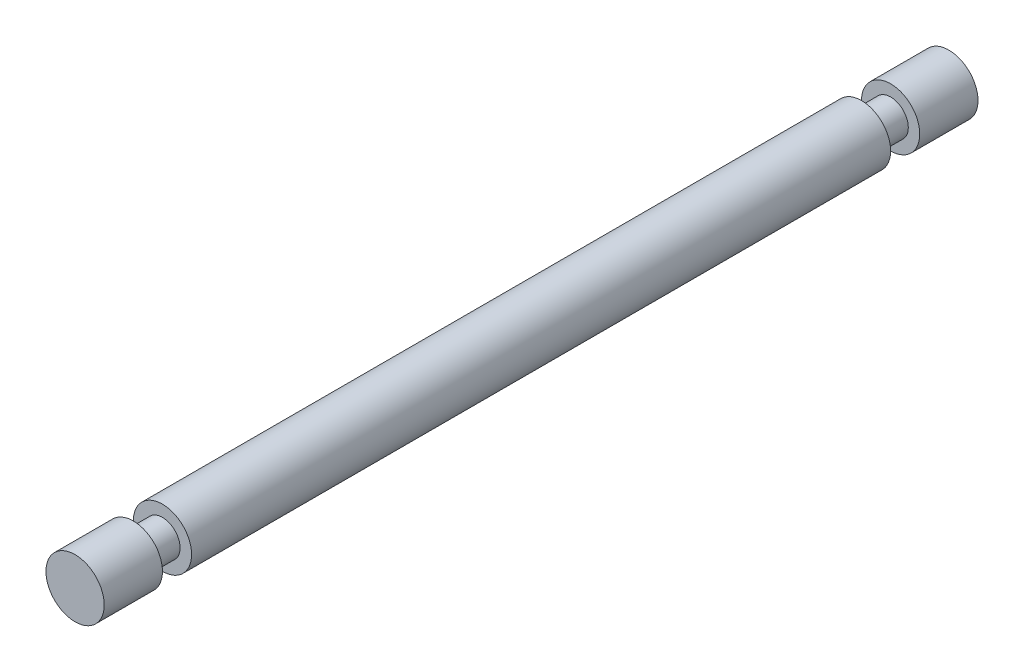
SolidWorks part; units mm, degrees
ref_plane "Front Plane" through (0, 0, 0) normal (0, 0, 1) x (1, 0, 0)
ref_plane "Top Plane" through (0, 0, 0) normal (0, 1, 0) x (1, 0, 0)
ref_plane "Right Plane" through (0, 0, 0) normal (1, 0, 0) x (0, 0, -1)
sketch "Sketch2" plane through (0, 0, 0) normal (0, 1, 0) x (1, 0, 0)
  line L1 (0, 0) -> (1.27, 0)
  line L2 (0, 0) -> (0, 38.1)
  line L3 (0, 38.1) -> (1.27, 38.1)
  line L4 (1.27, 0) -> (1.27, 38.1)
  dimension "D1" = 1.27
  dimension "D2" = 38.1
revolve "Revolve1" add sketch "Sketch2" angle 360 about L2
sketch "Sketch3" plane through (0, 0, 0) normal (0, 1, 0) x (1, 0, 0)
  line L0 (1.27, 2.54) -> (0.7706, 2.54)
  line L1 (1.27, 0) -> (1.27, 38.1) construction
  line L2 (0.7706, 2.54) -> (0.7706, 3.81)
  line L3 (0.7706, 3.81) -> (1.27, 3.81)
  line L4 (1.27, 3.81) -> (1.27, 2.54)
  line L5 (-1.27, 0) -> (1.27, 0) construction
  line L6 (0, 0) -> (0, 4.6043) construction
  dimension "D1" = 0.4994
  dimension "D2" = 2.54
  dimension "D3" = 1.27
revolve "Cut-Revolve1" cut sketch "Sketch3" angle 360 about L6
ref_plane "Mirror Point" through (0, 0, -19.05) normal (0, 0, 1) x (1, 0, 0)
mirror "Mirror1" about plane through (0, 0, -19.05) normal (0, 0, 1) of "Cut-Revolve1"
